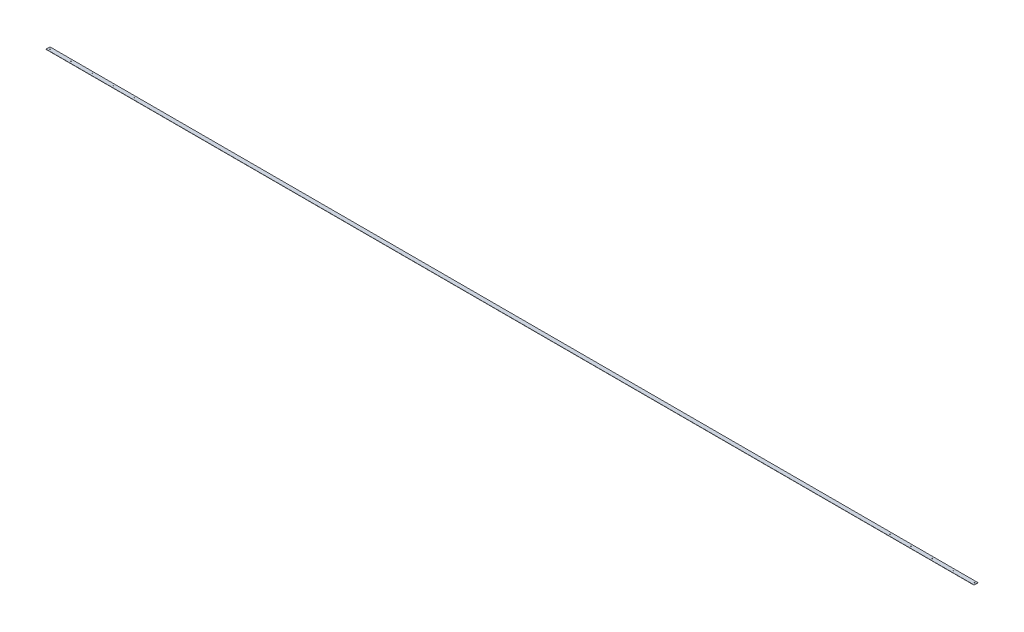
SolidWorks part; units mm, degrees
material "5052-H32"
ref_plane "Front Plane" through (0, 0, 0) normal (0, 0, 1) x (1, 0, 0)
ref_plane "Top Plane" through (0, 0, 0) normal (0, 1, 0) x (1, 0, 0)
ref_plane "Right Plane" through (0, 0, 0) normal (1, 0, 0) x (0, 0, -1)
sketch "Sketch1" plane through (0, 0, 0) normal (0, 1, 0) x (1, 0, 0)
  line L1 (4679.25, -20) -> (-4679.25, -20)
  line L2 (4679.25, -20) -> (4679.25, 20)
  line L3 (4679.25, 20) -> (-4679.25, 20)
  line L4 (-4679.25, -20) -> (-4679.25, 20)
  line L5 (4679.25, -20) -> (-4679.25, 20) construction
  line L6 (4679.25, 20) -> (-4679.25, -20) construction
  point P0 (0, 0)
  dimension "D1" = 40
  dimension "D2" = 9358.5
extrude "Boss-Extrude1" add sketch "Sketch1" along normal blind 2
sketch "Sketch2" plane through (0, 2, 0) normal (0, 1, 0) x (1, 0, 0)
  line L0 (-4679.25, -20) -> (4679.25, -20) construction
  line L1 (-4679.25, 20) -> (-4679.25, -20) construction
  line L2 (4679.25, -20) -> (4679.25, 20) construction
  circle A0 centre (-4659.25, 0) radius 3.4
  circle A1 centre (-4446.75, 0) radius 3.4
  circle A2 centre (-4234.25, 0) radius 3.4
  circle A3 centre (-4021.75, 0) radius 3.4
  circle A4 centre (-3809.25, 0) radius 3.4
  circle A5 centre (4662.25, 0) radius 3.4
  circle A6 centre (4449.75, 0) radius 3.4
  circle A7 centre (4237.25, 0) radius 3.4
  circle A8 centre (4024.75, 0) radius 3.4
  circle A9 centre (3812.25, 0) radius 3.4
  dimension "D1" = 6.8
  dimension "D5" = 212.5
  dimension "D8" = 5
  dimension "D2" = 20
  dimension "D3" = 20
  dimension "D6" = 17
  dimension "D7" = 20
  dimension "D9" = 212.5
  dimension "D4" = 5
extrude "Cut-Extrude1" cut sketch "Sketch2" against normal blind 10
